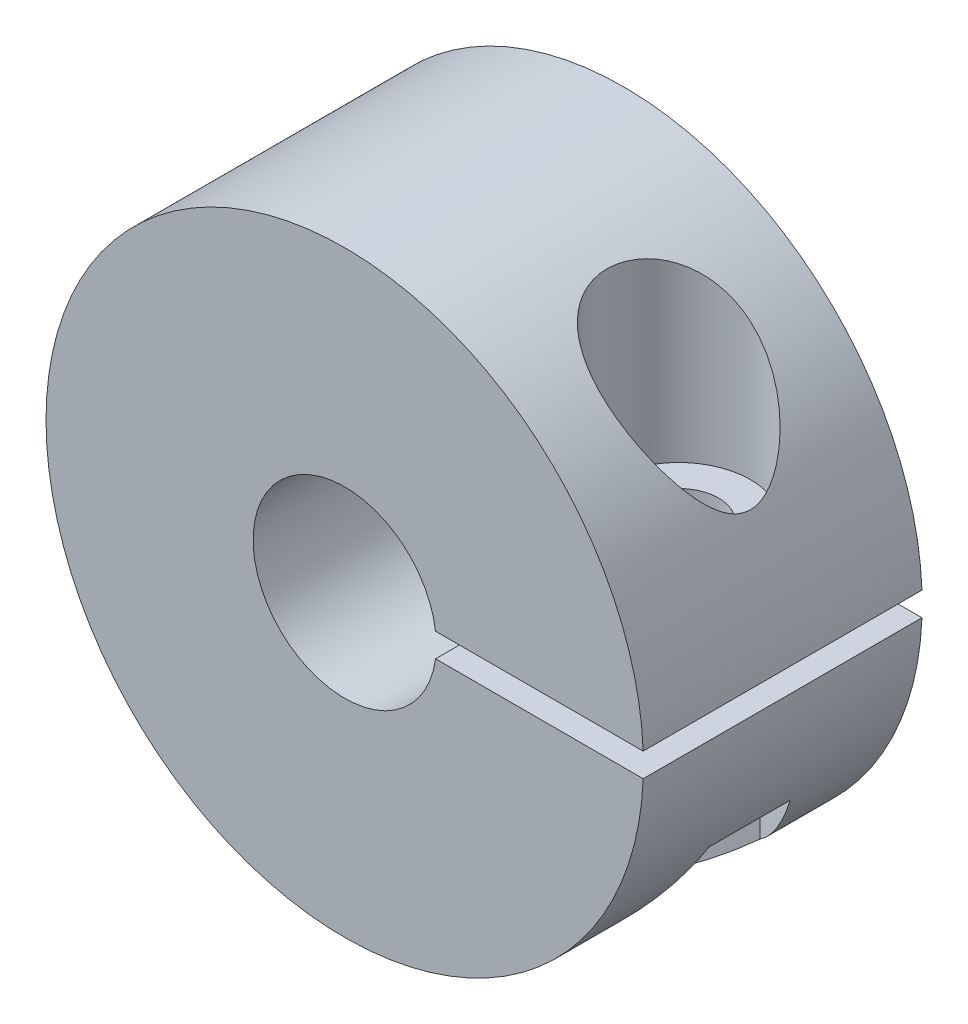
SolidWorks part; units mm, degrees
ref_plane "Front Plane" through (0, 0, 0) normal (0, 0, 1) x (1, 0, 0)
ref_plane "Top Plane" through (0, 0, 0) normal (0, 1, 0) x (1, 0, 0)
ref_plane "Right Plane" through (0, 0, 0) normal (1, 0, 0) x (0, 0, -1)
sketch "Sketch1" plane through (0, 0, 0) normal (0, 0, 1) x (1, 0, 0)
  circle A0 centre (0, 0) radius 4.6
  circle A1 centre (0, 0) radius 15
  dimension "D1" = 9.2
  dimension "D2" = 30
extrude "Boss-Extrude1" add sketch "Sketch1" along normal blind 14
sketch "Sketch2" plane through (0, 0, 14) normal (0, 0, 1) x (1, 0, 0)
  line L1 (3.6, 0.6) -> (16, 0.6)
  line L2 (3.6, 0.6) -> (3.6, -0.6)
  line L3 (3.6, -0.6) -> (16, -0.6)
  line L4 (16, 0.6) -> (16, -0.6)
  line L5 (3.6, 0.6) -> (16, -0.6) construction
  line L6 (3.6, -0.6) -> (16, 0.6) construction
  circle A0 centre (0, 0) radius 4.6 construction
  circle A1 centre (0, 0) radius 15 construction
  point P0 (9.8, 0)
  point P5 (3.6, 0)
  point P6 (0, 0)
  point P10 (4.6, 0)
  point P11 (15, 0)
  point P14 (16, 0)
  point P15 (15.9565, -0.5)
  point P16 (0, 0)
  point P17 (0, 0)
  point P18 (0, 0)
  dimension "D2" = 1
  dimension "D1" = 1.2
  dimension "D3" = 1
extrude "Cut-Extrude1" cut sketch "Sketch2" against normal through all
sketch "Sketch3" plane through (0, 0, 0) normal (0, 1, 0) x (1, 0, 0)
  line L0 (4.5607, -14) -> (14.988, 0) construction
  line L1 (14.988, 0) -> (14.988, -14) construction
  line L2 (14.988, -14) -> (4.5607, 0) construction
  line L4 (4.5607, -14) -> (14.988, -14)
  line L5 (4.5607, 0) -> (4.5607, -14)
  line L6 (14.988, 0) -> (4.5607, 0)
  line L7 (14.988, -14) -> (14.988, 0)
  line L8 (4.5607, -14) -> (14.988, -14) construction
  line L9 (4.5607, 0) -> (4.5607, -14) construction
  line L10 (14.988, 0) -> (4.5607, 0) construction
  line L11 (14.988, -14) -> (14.988, 0) construction
  circle A0 centre (9.7743, -7) radius 2
  dimension "D2" = 4
  dimension "D1" = 0
extrude "Cut-Extrude2" cut sketch "Sketch3" against normal through all both and the other way through all
ref_plane "Plane1" through (0, 4.5, 0) normal (0, 1, 0) x (1, 0, 0)
sketch "Sketch4" plane through (0, 4.5, 0) normal (0, 1, 0) x (1, 0, 0)
  circle A0 centre (9.7743, -7) radius 3.6
  dimension "D1" = 7.2
extrude "Cut-Extrude3" cut sketch "Sketch4" along normal up to next
ref_plane "Plane2" through (0, -4.5, 0) normal (0, 1, 0) x (1, 0, 0)
sketch "Sketch5" plane through (0, -4.5, 0) normal (0, 1, 0) x (1, 0, 0)
  line L1 (6.2297, -9.0589) -> (9.7851, -11.0992)
  line L2 (9.7851, -11.0992) -> (13.3297, -9.0403)
  line L3 (13.3297, -9.0403) -> (13.319, -4.9411)
  line L4 (13.319, -4.9411) -> (9.7636, -2.9008)
  line L5 (9.7636, -2.9008) -> (6.219, -4.9597)
  line L6 (6.219, -4.9597) -> (6.2297, -9.0589)
  circle A0 centre (9.7743, -7) radius 3.55 construction
  point P1 (13.3288, -9.0555)
  dimension "D1" = 7.1
extrude "Cut-Extrude4" cut sketch "Sketch5" against normal up to next
